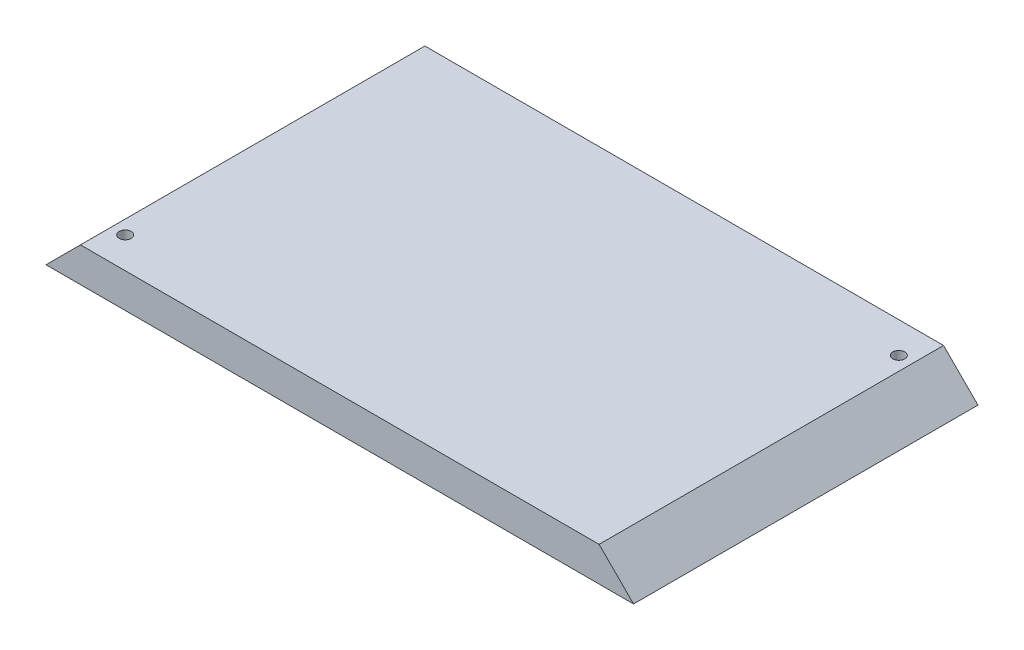
SolidWorks part; units mm, degrees
ref_plane "Front Plane" through (0, 0, 0) normal (0, 0, 1) x (1, 0, 0)
ref_plane "Top Plane" through (0, 0, 0) normal (0, 1, 0) x (1, 0, 0)
ref_plane "Right Plane" through (0, 0, 0) normal (1, 0, 0) x (0, 0, -1)
sketch "Sketch3" plane through (0, 0, 0) normal (0, 1, 0) x (1, 0, 0)
  line L1 (-77.0253, 25.8878) -> (73.5547, 25.8878)
  line L2 (-77.0253, 25.8878) -> (-77.0253, -74.1122)
  line L3 (-77.0253, -74.1122) -> (73.5547, -74.1122)
  line L4 (73.5547, 25.8878) -> (73.5547, -74.1122)
  point P4 (0, 0)
  point P5 (0, 0)
extrude "Boss-Extrude1" add sketch "Sketch3" along normal blind 10
draft "Draft1" type of draft neutral plane draft angle 45 faces to draft 2 face at (73.5547, 5, 24.1122) face at (-77.0253, 5, 24.1122) neutral plane through (0, 10, 0) neutral plane normal (0, 1, 0) parameters "D1"=45
sketch "Sketch4" plane through (0, 10, 0) normal (0, 1, 0) x (1, 0, 0)
  line L0 (-60.8953, 16.8878) -> (73.5547, 16.8878) construction
  line L1 (73.5547, -74.1122) -> (73.5547, 25.8878) construction
  line L2 (73.5547, 16.8878) -> (69.5547, 16.8878)
  line L3 (57.9547, -65.1122) -> (-77.0253, -65.1122) construction
  line L4 (-77.0253, 25.8878) -> (-77.0253, -74.1122) construction
  line L5 (-77.0253, -65.1122) -> (-73.0253, -65.1122) construction
  circle A0 centre (69.5547, 16.8878) radius 1.75
  circle A1 centre (-73.0253, -65.1122) radius 1.75
  point P11 (0, 0)
  point P12 (0, 0)
extrude "Cut-Extrude1" cut sketch "Sketch4" against normal blind 15
